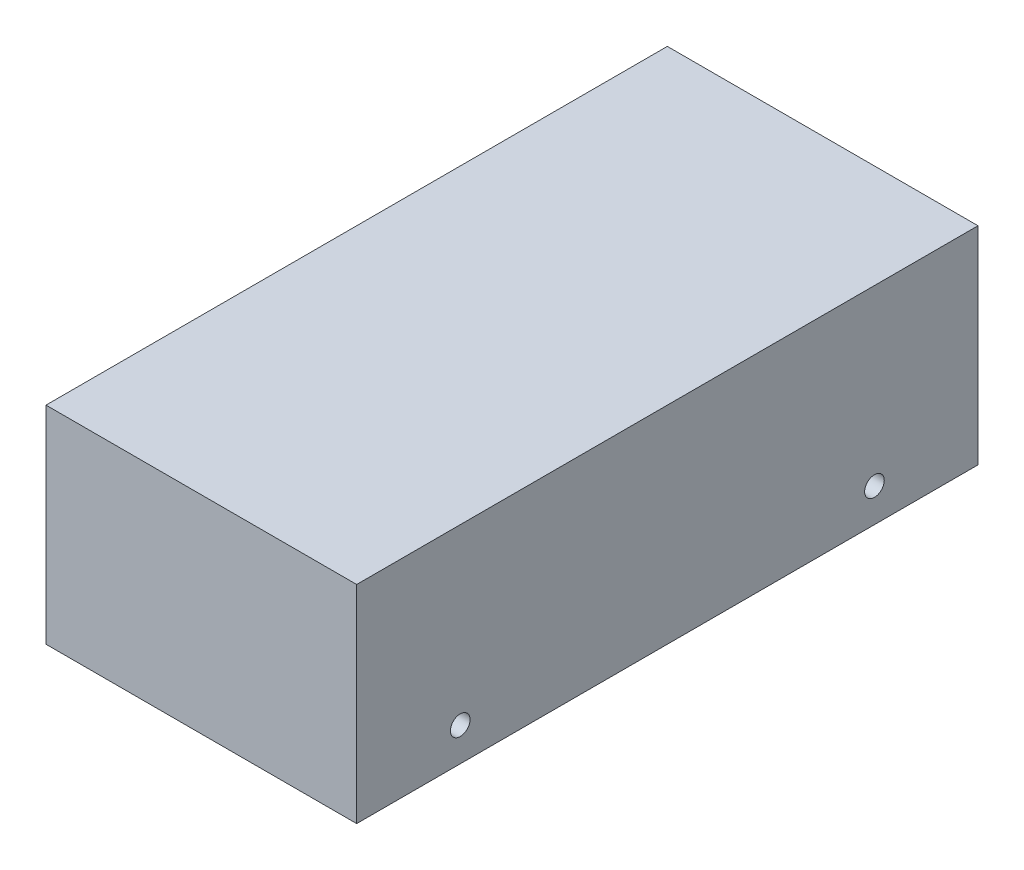
SolidWorks part; units mm, degrees
ref_plane "Front Plane" through (0, 0, 0) normal (0, 0, 1) x (1, 0, 0)
ref_plane "Top Plane" through (0, 0, 0) normal (0, 1, 0) x (1, 0, 0)
ref_plane "Right Plane" through (0, 0, 0) normal (1, 0, 0) x (0, 0, -1)
sketch "Sketch1" plane through (0, 0, 0) normal (0, 0, 1) x (1, 0, 0)
  line L0 (-37.5, 25) -> (37.5, -25) construction
  line L1 (-37.5, 25) -> (37.5, 25)
  line L2 (-37.5, 25) -> (-37.5, -25)
  line L3 (-37.5, -25) -> (37.5, -25)
  line L4 (37.5, 25) -> (37.5, -25)
  dimension "D1" = 75
  dimension "D2" = 50
extrude "Boss-Extrude1" add sketch "Sketch1" along normal blind 150
sketch "Sketch2" plane through (37.5, 0, 0) normal (1, 0, 0) x (0, 0, -1)
  line L0 (-125, -16.9192) -> (-25, -16.9192) construction
  line L1 (-150, -25) -> (-150, 25) construction
  line L2 (0, -25) -> (0, 25) construction
  circle A0 centre (-125, -16.9192) radius 2.3696
  circle A1 centre (-25, -16.9192) radius 2.3696
  dimension "D1" = 25
  dimension "D2" = 25
sketch "Sketch3" plane through (-37.5, 0, 0) normal (-1, 0, 0) x (0, 0, 1)
  circle A1 centre (25, -16.9192) radius 2.3696
  circle A2 centre (25, -16.9192) radius 2.3696
  circle A3 centre (125, -16.9192) radius 2.3696
  circle A4 centre (125, -16.9192) radius 2.3696
  dimension "D1" = 0
  dimension "D2" = 0
extrude "Cut-Extrude1" cut sketch "Sketch2" against normal blind 10
extrude "Cut-Extrude2" cut sketch "Sketch3" against normal blind 10
